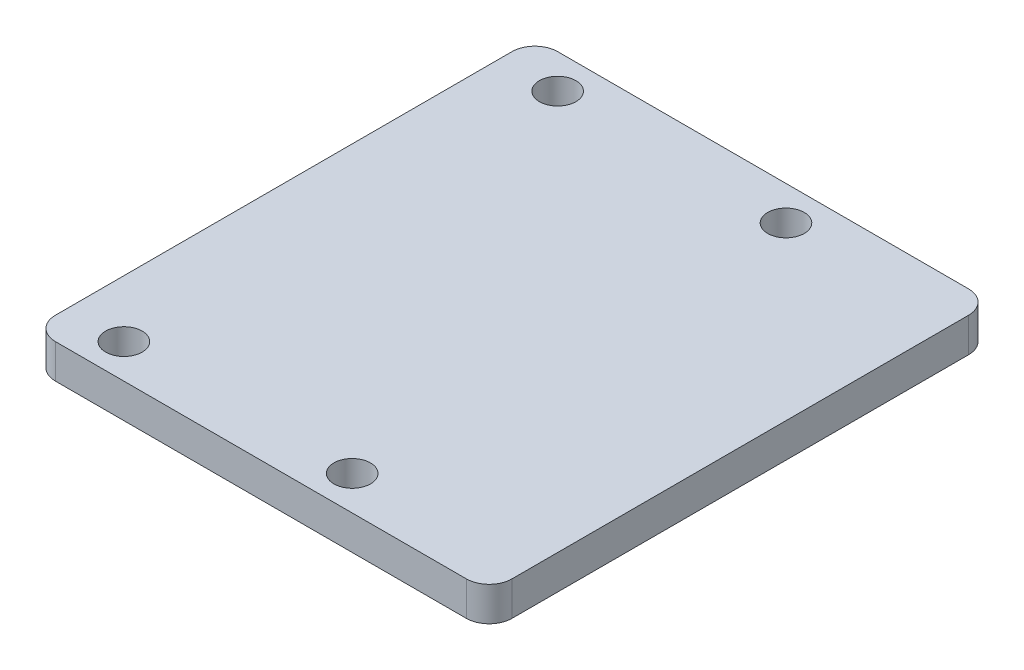
SolidWorks part; units mm, degrees
ref_plane "前视基准面" through (0, 0, 0) normal (0, 0, 1) x (1, 0, 0)
ref_plane "上视基准面" through (0, 0, 0) normal (0, 1, 0) x (1, 0, 0)
ref_plane "右视基准面" through (0, 0, 0) normal (1, 0, 0) x (0, 0, -1)
other "Configuration Table"
sketch "草图1" plane through (0, 0, 0) normal (0, 1, 0) x (1, 0, 0)
  line L0 (0, -16) -> (0, 0) construction
  line L1 (-20, 22) -> (20, 22)
  line L2 (-20, 22) -> (-20, -22)
  line L3 (-20, -22) -> (20, -22)
  line L4 (20, 22) -> (20, -22)
  line L5 (-20, 22) -> (20, -22) construction
  line L6 (-20, -22) -> (20, 22) construction
  line L7 (-20, -16) -> (20, -16) construction
  line L8 (-20, -16) -> (-20, -22) construction
  line L9 (-20, -22) -> (20, -22) construction
  line L10 (20, -16) -> (20, -22) construction
  line L11 (-20, -19) -> (20, -19) construction
  line L12 (-20, 0) -> (0, 0) construction
  circle A0 centre (-15, -19) radius 1.6
  circle A1 centre (5, -19) radius 1.6
  circle A2 centre (5, 19) radius 1.6
  circle A3 centre (-15, 19) radius 1.6
  point P0 (0, 0)
  dimension "D7" = 3.2
  dimension "D1" = 44
  dimension "D2" = 40
  dimension "D3" = 40
  dimension "D4" = 6
  dimension "D5" = 5
  dimension "D6" = 20
extrude "凸台-拉伸1" add sketch "草图1" along normal blind 3
fillet "圆角1" radius 2 4 edges at (20, 1.5, 22) (-20, 1.5, -22) (20, 1.5, -22) (-20, 1.5, 22)
